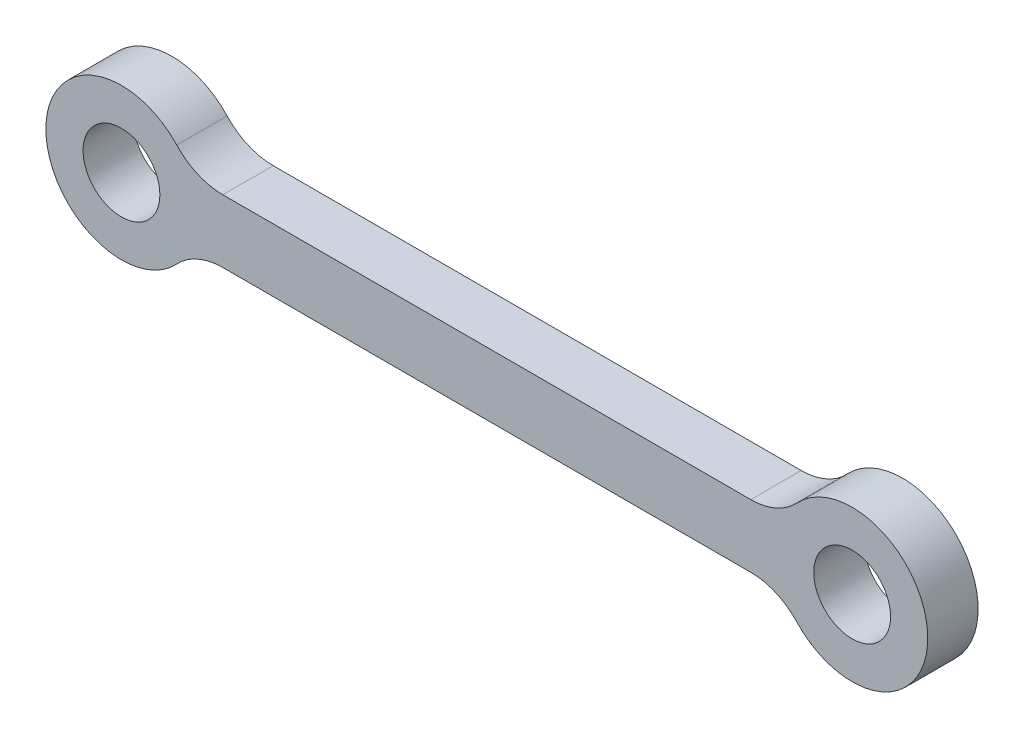
SolidWorks part; units mm, degrees
material "7050-T73510"
ref_plane "前视基准面" through (0, 0, 0) normal (0, 0, 1) x (1, 0, 0)
ref_plane "上视基准面" through (0, 0, 0) normal (0, 1, 0) x (1, 0, 0)
ref_plane "右视基准面" through (0, 0, 0) normal (1, 0, 0) x (0, 0, -1)
sketch "草图1" plane through (0, 0, 0) normal (0, 0, 1) x (1, 0, 0)
  line L0 (-29, 0) -> (29, 0) construction
  line L1 (-29, -6) -> (29, -6)
  line L2 (-29, 6) -> (29, 6)
  arc A0 (-29, -6) -> (-29, 6) centre (-29, 0) cw
  arc A1 (29, -6) -> (29, 6) centre (29, 0) ccw
  circle A2 centre (-29, 0) radius 3.05
  circle A3 centre (29, 0) radius 3.05
  point P4 (0, 0)
  dimension "D4" = 6.1
  dimension "D5" = 6.1
  dimension "D1" = 58
  dimension "D2" = 6
  dimension "D3" = 6
extrude "凸台-拉伸1" add sketch "草图1" along normal mid plane 4
sketch "草图2" plane through (0, 0, 2) normal (0, 0, 1) x (1, 0, 0)
  line L0 (-29, 0) -> (29, 0)
  line L1 (-29, -2.5) -> (29, -2.5)
  line L2 (-29, 2.5) -> (29, 2.5)
  line L3 (-29, 6) -> (29, 6)
  line L4 (-29, -6) -> (29, -6)
  arc A0 (29, -6) -> (29, 6) centre (29, 0) ccw construction
  arc A1 (-29, 6) -> (-29, -6) centre (-29, 0) ccw construction
  arc A2 (23.5456, -2.5) -> (23.5456, 2.5) centre (29, 0) ccw
  arc A3 (-23.5456, 2.5) -> (-23.5456, -2.5) centre (-29, 0) ccw
  arc A4 (-29, -2.5) -> (-29, 2.5) centre (-29, 0) cw
  arc A5 (29, -2.5) -> (29, 2.5) centre (29, 0) ccw
  line M3 (-29, -6) -> (29, -6)
  line M5 (29, 6) -> (-29, 6)
  dimension "D1" = 2.5
  dimension "D2" = 2.5
extrude "切除-拉伸1" cut sketch "草图2" against normal blind 4.2 contours A3 A2 L1 M3 | A3 L2 A2 M5
fillet "圆角1" radius 5 4 edges at (-23.5456, -2.5, 0) (23.5456, -2.5, 0) (23.5456, 2.5, 0) (-23.5456, 2.5, 0)
sketch "草图3" plane through (0, 0, 0) normal (0, 0, 1) x (1, 0, 0)
  line L1 (-23, 3.5) -> (23, 3.5)
  line L2 (23, 3.5) -> (23, 0)
  line L3 (23, 0) -> (-23, 0) construction
  line L4 (-23, 0) -> (-23, 3.5)
  line L5 (-23, 0) -> (23, 0)
  point P0 (0, 0)
  dimension "D1" = 3.5
  dimension "D2" = 46
